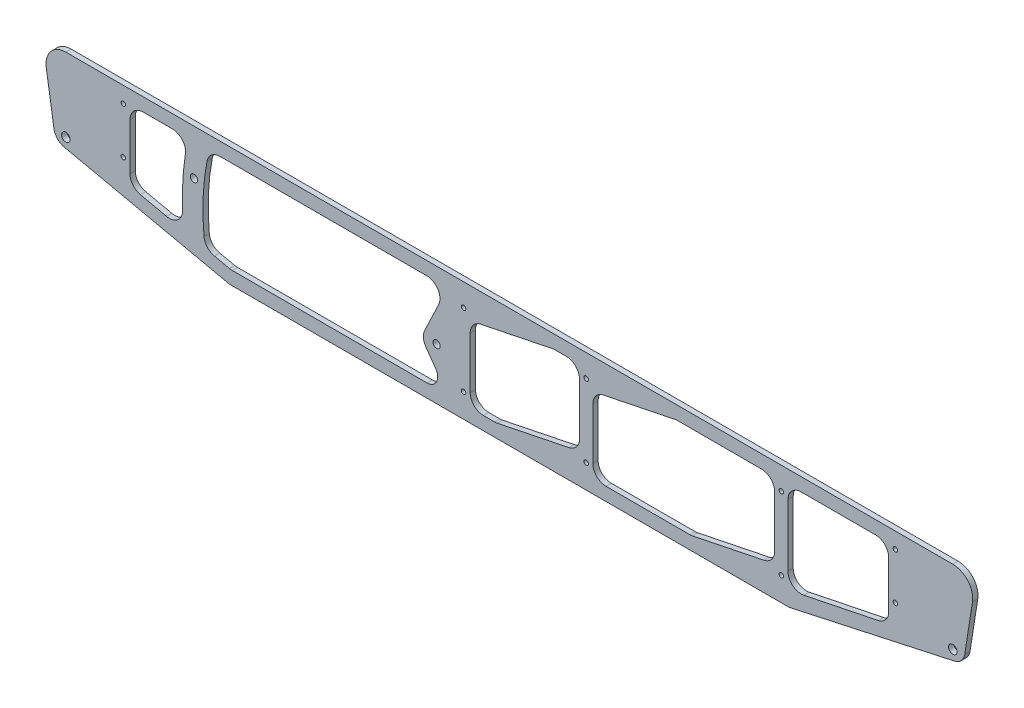
SolidWorks part; units mm, degrees
material "Сплав 2024"
ref_plane "Спереди" through (0, 0, 0) normal (0, 0, 1) x (1, 0, 0)
ref_plane "Сверху" through (0, 0, 0) normal (0, 1, 0) x (1, 0, 0)
ref_plane "Справа" through (0, 0, 0) normal (1, 0, 0) x (0, 0, -1)
sketch "Эскиз1" plane through (0, 0, 0) normal (0, 0, 1) x (1, 0, 0)
  line L0 (-349.8183, 27.6724) -> (-342.9109, -16.3036)
  line L1 (-350, 45) -> (350, 45) construction
  line L2 (-350, 45) -> (-350, -45) construction
  line L3 (-350, -45) -> (350, -45) construction
  line L4 (350, 45) -> (350, -45) construction
  line L5 (-350, 45) -> (350, -45) construction
  line L6 (-350, -45) -> (350, 45) construction
  line L7 (-342.9109, -16.3036) -> (-211.4811, -45)
  line L9 (0, 62.4154) -> (0, -74.3401) construction
  line L10 (-211.4811, -45) -> (211.4811, -45)
  line L12 (-335, 45) -> (335, 45)
  line L15 (342.9109, -16.3036) -> (211.4811, -45)
  line L16 (349.8183, 27.6724) -> (342.9109, -16.3036)
  arc A0 (-335, 45) -> (-349.8183, 27.6724) centre (-335, 30) ccw
  arc A1 (335, 45) -> (349.8183, 27.6724) centre (335, 30) cw
  circle A2 centre (-335, -10.6353) radius 3.25
  circle A3 centre (335, -10.6353) radius 3.25
  point P0 (0, 0)
  point P20 (0, 45)
  point P21 (0, -45)
  dimension "D3" = 30
  dimension "D4" = 6.5
  dimension "D1" = 700
  dimension "D2" = 90
extrude "Бобышка-Вытянуть1" add sketch "Эскиз1" along normal blind 4
sketch "Эскиз2" plane through (0, 0, 4) normal (0, 0, 1) x (1, 0, 0)
  line L0 (0, 49.4785) -> (0, -75.5602) construction
  line L1 (-350, 30) -> (-320, 30) construction
  line L2 (-335, 45) -> (-335, 15) construction
  line L3 (335, 45) -> (335, 15) construction
  line L4 (350, 30) -> (320, 30) construction
  circle A0 centre (-335, 30) radius 15 construction
  arc A1 (-335, 45) -> (-349.8183, 27.6724) centre (-335, 30) ccw construction
  circle A2 centre (-335, 30) radius 10 construction
  circle A4 centre (335, 30) radius 10 construction
  circle A5 centre (335, 30) radius 15 construction
  dimension "D2" = 20
hole_wizard "Отверстие с зазором M51" positions "Эскиз4" profile "Эскиз3" hole size "M5" standard "Ansi Metric"
sketch "Эскиз4" plane through (0, 0, 4) normal (0, 0, 1) x (1, 0, 0)
  line L0 (-335, 45) -> (-335, 15) construction
  line L1 (-350, 30) -> (-320, 30) construction
  line L2 (350, 30) -> (320, 30) construction
  line L3 (335, 45) -> (335, 15) construction
  circle A0 centre (-335, 30) radius 10 construction
  circle A1 centre (335, 30) radius 10 construction
  point P0 (-335, 40)
  point P6 (-345, 30)
  point P10 (-335, 20)
  point P12 (-325, 30)
  point P34 (325, 30)
  point P40 (335, 40)
  point P44 (345, 30)
  point P46 (335, 20)
sketch "Эскиз3" plane through (-335, 40, 4) normal (1, 0, 0) x (0, -1, 0)
  line L0 (0, 0) -> (0, 4)
  line L1 (0, 4) -> (2.75, 4)
  line L2 (2.75, 4) -> (2.75, 0)
  line L5 (2.75, 0) -> (0, 0)
  line L11 (0, -6.35) -> (0, 107.95) construction
  dimension "Диаметр сквозного отверстия" = 5.5
  dimension "Глубина сквозного отверстия" = 4
sketch "Эскиз7" plane through (0, 0, 0) normal (0, 0, -1) x (-1, 0, 0)
  line L0 (211.4811, -45) -> (-211.4811, -45) construction
  arc A0 (349.8183, 27.6724) -> (335, 45) centre (335, 30) ccw construction
  point P0 (55, -6)
  point P4 (238.23, 10.84)
  dimension "D1" = 183.23
  dimension "D2" = 16.84
  dimension "D3" = 280
  dimension "D4" = 39
hole_wizard "Отверстие с зазором M52" positions "Эскиз9" profile "Эскиз8" hole size "M5" standard "Ansi Metric" end condition through all
sketch "Эскиз9" plane through (0, 0, 0) normal (0, 0, -1) x (-1, 0, 0)
  point P0 (55, -6)
  point P3 (238.23, 10.84)
sketch "Эскиз8" plane through (-55, -6, 0) normal (1, 0, 0) x (0, 1, 0)
  line L0 (0, 0) -> (0, 4)
  line L1 (0, 4) -> (2.75, 4)
  line L2 (2.75, 4) -> (2.75, 0)
  line L5 (2.75, 0) -> (0, 0)
  line L11 (0, -6.35) -> (0, 107.95) construction
  dimension "Диаметр сквозного отверстия" = 5.5
  dimension "Глубина сквозного отверстия" = 4
sketch "Эскиз10" plane through (0, 0, 4) normal (0, 0, 1) x (1, 0, 0)
  line L0 (-286.5713, 35) -> (-242.5713, 35)
  line L1 (335, 45) -> (-335, 45) construction
  line L2 (-286.5713, 35) -> (-286.5713, -18.3692)
  line L3 (-286.5713, -18.3692) -> (-245.8185, -27.2672)
  line L4 (0, 45) -> (0, -45) construction
  line L5 (-342.9109, -16.3036) -> (-211.4811, -45) construction
  line L6 (-226.6719, 35) -> (-46.5878, 35)
  line L7 (-210.4021, -35) -> (-46.5878, -35)
  line L8 (-211.4811, -45) -> (211.4811, -45) construction
  line L9 (-210.4021, -35) -> (-229.7525, -30.775)
  line L10 (-46.5878, 35) -> (-64.032, -1.7078)
  line L11 (-46.5878, -35) -> (-63.1395, -11.8093)
  line L12 (286.5713, 35) -> (286.5713, -18.3692)
  line L13 (286.5713, -18.3692) -> (210.4021, -34)
  line L14 (286.5713, 35) -> (210.4021, 35)
  line L15 (210.4021, 35) -> (210.4021, -34)
  line L16 (210.4021, -42) -> (210.4021, 43) construction
  line L17 (200.4021, 35) -> (126.1451, 35)
  line L18 (200.4021, -42) -> (200.4021, 43) construction
  line L19 (-29.5979, -42) -> (-29.5979, 43) construction
  line L20 (-29.5979, 22.0494) -> (-29.5979, -35)
  line L21 (-29.5979, -35) -> (-10.0721, -35)
  line L22 (200.4021, -22.0494) -> (200.4021, 35)
  line L23 (53.0365, 35) -> (53.0365, -22.0494)
  line L24 (63.0365, 22.0494) -> (63.0365, -35)
  line L25 (33.5107, 35) -> (-29.5979, 22.0494)
  line L26 (200.4021, -22.0494) -> (137.2934, -35)
  line L28 (63.0365, -35) -> (137.2934, -35)
  line L29 (126.1451, 35) -> (63.0365, 22.0494)
  line L30 (53.0365, -22.0494) -> (-10.0721, -35)
  line L34 (53.0365, 35) -> (33.5107, 35)
  arc A0 (-64.032, -1.7078) -> (-63.1395, -11.8093) centre (-55, -6) ccw
  arc A2 (-242.5713, 35) -> (-245.8185, -27.2672) centre (-55, -6) ccw
  arc A3 (-226.6719, 35) -> (-229.7525, -30.775) centre (-55, -6) ccw
  dimension "D4" = 384
  dimension "D5" = 353
  dimension "D2" = 20
  dimension "D1" = 10
  dimension "D3" = 10
  dimension "D6" = 10
  dimension "D7" = 10
  dimension "D8" = 10
  dimension "D9" = 44
  dimension "D10" = 10
  dimension "D11" = 57.0494
extrude "Вырез-Вытянуть3" cut sketch "Эскиз10" against normal through all
fillet "Скругление2" radius 10 16 edges at (-46.5878, 35, 2) (-210.4021, -35, 2) (-229.7525, -30.775, 2) (-226.6719, 35, 2) (-242.5713, 35, 2) (-245.8185, -27.2672, 2) (-286.5713, -18.3692, 2) (-286.5713, 35, 2) (-342.9109, -16.3036, 2) (-211.4811, -45, 2) (211.4811, -45, 2) (342.9109, -16.3036, 2) (286.5713, 35, 2) (286.5713, -18.3692, 2) (210.4021, 35, 2) (210.4021, -34, 2)
fillet "Скругление3" radius 10 12 edges at (-29.5979, -35, 2) (200.4021, 35, 2) (53.0365, 35, 2) (200.4021, -22.0494, 2) (137.2934, -35, 2) (33.5107, 35, 2) (-29.5979, 22.0494, 2) (63.0365, -35, 2) (126.1451, 35, 2) (63.0365, 22.0494, 2) (53.0365, -22.0494, 2) (-10.0721, -35, 2)
sketch "Эскиз11" plane through (0, 0, 4) normal (0, 0, 1) x (1, 0, 0)
  line L0 (205.4021, 45) -> (205.4021, -45) construction
  line L1 (335, 45) -> (-335, 45) construction
  line L2 (-210.4021, -45) -> (210.4021, -45) construction
  line L3 (200.4021, -13.8931) -> (200.4021, 25) construction
  line L4 (199.8709, -27) -> (211.9144, -27) construction
  line L5 (202.3145, 28) -> (208.249, 28) construction
  line L6 (-34.5979, 45) -> (-34.5979, -45) construction
  line L7 (-29.5979, 13.8931) -> (-29.5979, -25) construction
  line L8 (-39.6608, -27) -> (-30.9685, -27) construction
  line L9 (-37.6326, 28) -> (-30.9685, 28) construction
  line L10 (291.5713, 36.1496) -> (291.5713, -11.5594) construction
  line L11 (286.5713, -10.2129) -> (286.5713, 25) construction
  line L12 (294.823, -2) -> (288.4097, -2) construction
  line L13 (294.823, 33) -> (288.4097, 33) construction
  line L14 (0, 45) -> (0, 71.0849) construction
  line L15 (-294.823, 33) -> (-288.4097, 33) construction
  line L16 (-294.823, -2) -> (-288.4097, -2) construction
  line L17 (-291.5713, 36.1496) -> (-291.5713, -11.5594) construction
  line L18 (58.0365, 45) -> (58.0365, -45) construction
  line L19 (53.0365, -13.8931) -> (53.0365, 25) construction
  line L20 (53.8048, -27) -> (63.1419, -27) construction
  line L21 (64.656, 28) -> (53.8048, 28) construction
  dimension "D1" = 5
  dimension "D2" = 18
  dimension "D3" = 55
  dimension "D4" = 5
  dimension "D5" = 18
  dimension "D6" = 55
  dimension "D7" = 5
  dimension "D8" = 35
  dimension "D9" = 5
  dimension "D10" = 18
  dimension "D11" = 55
hole_wizard "Отверстие с зазором M31" positions "Эскиз13" profile "Эскиз12" hole size "M3" standard "Ansi Metric" end condition through all
sketch "Эскиз13" plane through (0, 0, 4) normal (0, 0, 1) x (1, 0, 0)
  line L0 (-34.5979, 45) -> (-34.5979, -45) construction
  line L1 (-37.6326, 28) -> (-30.9685, 28) construction
  line L2 (-39.6608, -27) -> (-30.9685, -27) construction
  line L3 (205.4021, 45) -> (205.4021, -45) construction
  line L4 (199.8709, -27) -> (211.9144, -27) construction
  line L5 (202.3145, 28) -> (208.249, 28) construction
  line L6 (291.5713, 36.1496) -> (291.5713, -11.5594) construction
  line L7 (294.823, 33) -> (288.4097, 33) construction
  line L8 (294.823, -2) -> (288.4097, -2) construction
  line L9 (-294.823, -2) -> (-288.4097, -2) construction
  line L10 (-294.823, 33) -> (-288.4097, 33) construction
  line L11 (-291.5713, 36.1496) -> (-291.5713, -11.5594) construction
  line L12 (58.0365, 45) -> (58.0365, -45) construction
  line L13 (64.656, 28) -> (53.8048, 28) construction
  line L14 (53.8048, -27) -> (63.1419, -27) construction
  point P0 (-34.5979, 28)
  point P6 (-34.5979, -27)
  point P10 (205.4021, -27)
  point P16 (205.4021, 28)
  point P22 (291.5713, 33)
  point P28 (291.6163, -2)
  point P32 (-291.6163, -2)
  point P36 (-291.5713, 33)
  point P49 (58.0365, 28)
  point P55 (58.0365, -27)
sketch "Эскиз12" plane through (-34.5979, 28, 4) normal (1, 0, 0) x (0, -1, 0)
  line L0 (0, 0) -> (0, 4)
  line L1 (0, 4) -> (1.7, 4)
  line L2 (1.7, 4) -> (1.7, 0)
  line L5 (1.7, 0) -> (0, 0)
  line L11 (0, -6.35) -> (0, 107.95) construction
  dimension "Диаметр сквозного отверстия" = 3.4
  dimension "Глубина сквозного отверстия" = 4
sketch "Эскиз14" plane through (0, 0, 4) normal (0, 0, 1) x (1, 0, 0)
  line L0 (0, 59.2479) -> (0, -65.4566) construction
fillet "Скругление4" radius 8 1 edges at (-46.5878, -35, 2)
sketch "Эскиз15" plane through (0, 0, 0) normal (0, 0, 1) x (1, 0, 0)
  line L0 (-350, 50.324) -> (-350, -45) construction
  line L1 (-350, -45) -> (-206.5248, -45) construction
  line L2 (-210.4021, -45) -> (210.4021, -45) construction
  line L3 (350, 85.9671) -> (350, -45) construction
  arc A0 (-335, 45) -> (-349.8183, 27.6724) centre (-335, 30) ccw construction
  arc A1 (349.8183, 27.6724) -> (335, 45) centre (335, 30) ccw construction
